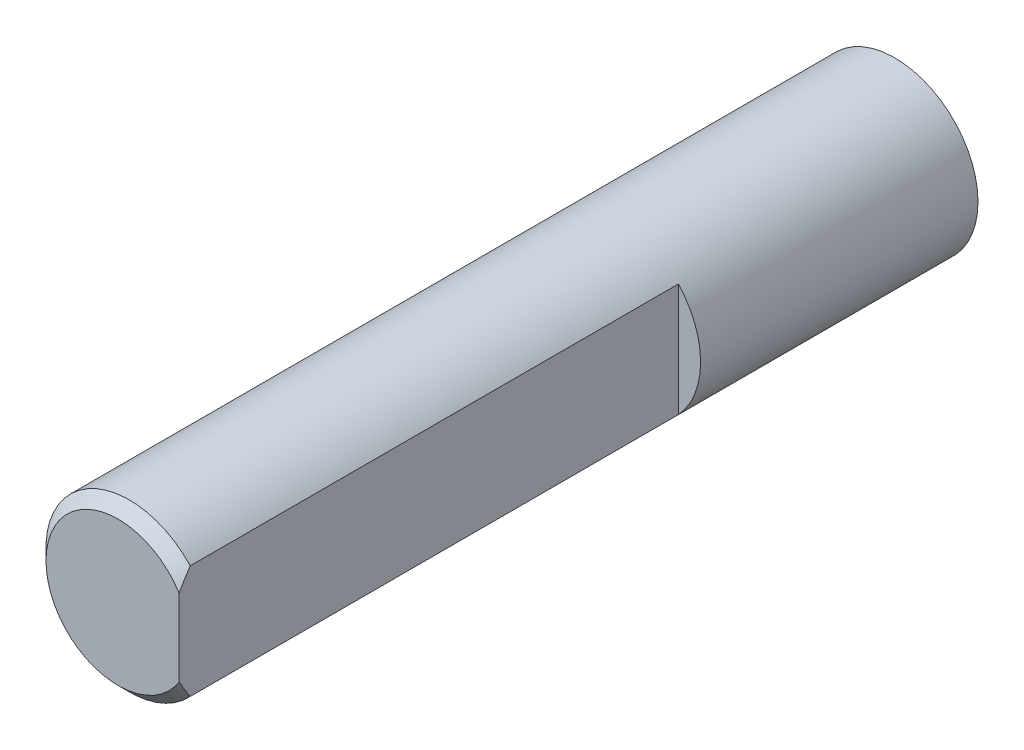
SolidWorks part; units mm, degrees
material "1060 Сплав"
ref_plane "Спереди" through (0, 0, 0) normal (0, 0, 1) x (1, 0, 0)
ref_plane "Сверху" through (0, 0, 0) normal (0, 1, 0) x (1, 0, 0)
ref_plane "Справа" through (0, 0, 0) normal (1, 0, 0) x (0, 0, -1)
sketch "Эскиз1" plane through (0, 0, 0) normal (0, 0, 1) x (1, 0, 0)
  circle A0 centre (0, 0) radius 1.5
  dimension "D1" = 3
extrude "Бобышка-Вытянуть1" add sketch "Эскиз1" along normal blind 5
sketch "Эскиз2" plane through (0, 0, 5) normal (0, 0, 1) x (1, 0, 0)
  line L0 (1.1, 1.0198) -> (1.1, -1.0198)
  circle A0 centre (0, 0) radius 1.5 construction
  circle A2 centre (0, 0) radius 1.5
  arc A3 (1.1, 1.0198) -> (1.1, -1.0198) centre (0, 0) ccw
  dimension "D1" = 1.1
  dimension "D2" = 0
extrude "Бобышка-Вытянуть2" add sketch "Эскиз2" along normal blind 9
chamfer "Фаска1" distance 0.2 angle 45 1 edges at (-1.5, 0, 14)
